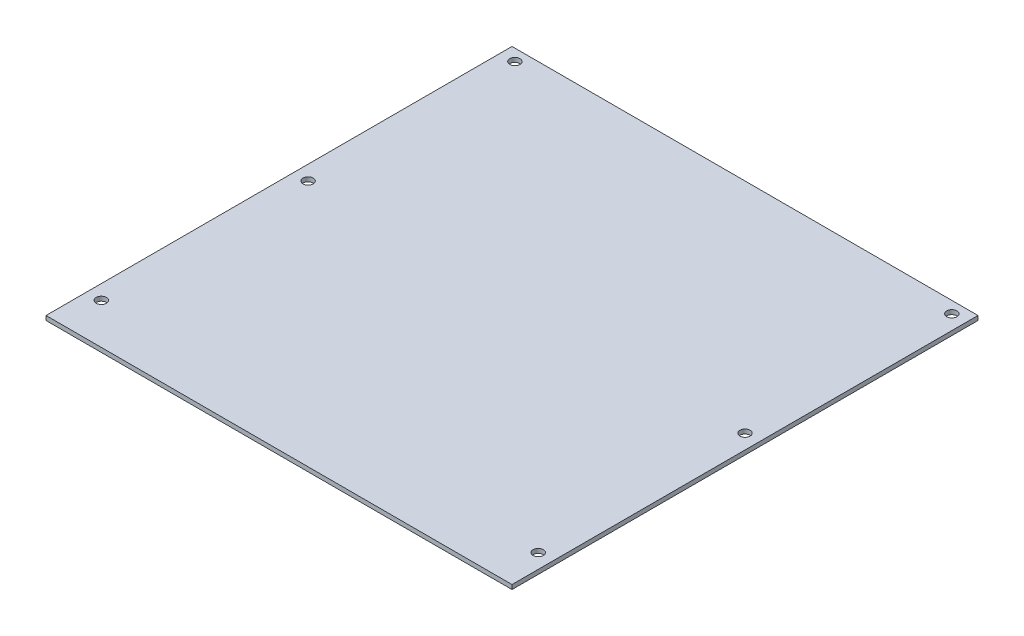
SolidWorks part; units mm, degrees
ref_plane "Alzado" through (0, 0, 0) normal (0, 0, 1) x (1, 0, 0)
ref_plane "Planta" through (0, 0, 0) normal (0, 1, 0) x (1, 0, 0)
ref_plane "Vista lateral" through (0, 0, 0) normal (1, 0, 0) x (0, 0, -1)
sketch "Croquis1" plane through (0, 0, 0) normal (0, 1, 0) x (1, 0, 0)
  line L0 (-80, 76) -> (-75, 76) construction
  line L1 (-80, 80) -> (80, 80)
  line L2 (-80, 80) -> (-80, -80)
  line L3 (-80, -80) -> (80, -80)
  line L4 (80, 80) -> (80, -80)
  line L5 (-80, 80) -> (80, -80) construction
  line L6 (-80, -80) -> (80, 80) construction
  line L7 (-75, 76) -> (75, 76) construction
  line L8 (75, 76) -> (80, 76) construction
  line L9 (0, 76) -> (0, 0) construction
  line L10 (0, 0) -> (-32.002, 0) construction
  line L11 (-75, 76) -> (-75, 5) construction
  line L12 (-75, 5) -> (-75, -66) construction
  line L13 (-75, -66) -> (75, -66) construction
  line L14 (75, -66) -> (75, 5) construction
  line L15 (75, 5) -> (75, 76) construction
  circle A0 centre (-75, 76) radius 1.75
  circle A1 centre (75, 76) radius 1.75
  circle A4 centre (-75, 5) radius 1.75
  circle A5 centre (-75, -66) radius 1.75
  circle A6 centre (75, -66) radius 1.75
  circle A7 centre (75, 5) radius 1.75
  point P0 (0, 0)
  dimension "D5" = 3.5
  dimension "D1" = 160
  dimension "D2" = 160
  dimension "D3" = 5
  dimension "D4" = 4
  dimension "D6" = 71
  dimension "D7" = 71
  dimension "D8" = 71
extrude "Saliente-Extruir1" add sketch "Croquis1" along normal blind 1.5
